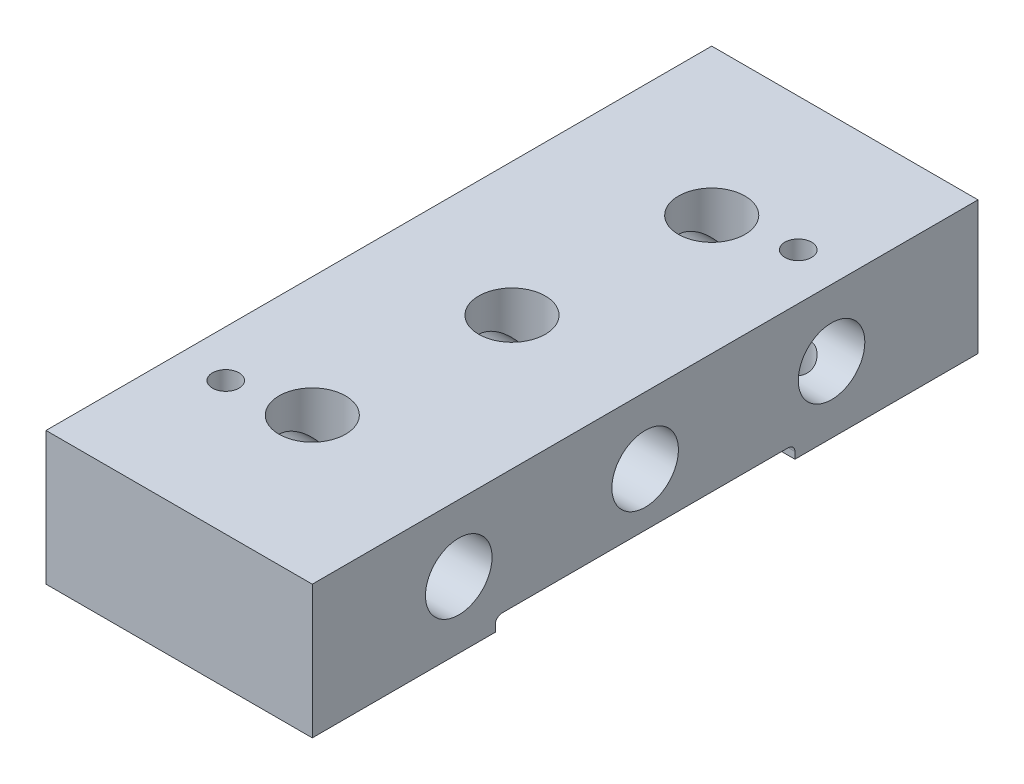
SolidWorks part; units mm, degrees
ref_plane "Plan de face" through (0, 0, 0) normal (0, 0, 1) x (1, 0, 0)
ref_plane "Plan de dessus" through (0, 0, 0) normal (0, 1, 0) x (1, 0, 0)
ref_plane "Plan de droite" through (0, 0, 0) normal (1, 0, 0) x (0, 0, -1)
sketch "Esquisse1" plane through (0, 0, 0) normal (0, 1, 0) x (1, 0, 0)
  line L0 (10, 50) -> (10, 0) construction
  line L1 (0, 0) -> (20, 0)
  line L2 (0, 0) -> (0, 50)
  line L3 (0, 50) -> (20, 50)
  line L4 (20, 0) -> (20, 50)
  line L5 (11, 39) -> (10, 39) construction
  line L6 (0.7507, 0.7524) -> (18.7507, 0.7524) construction
  line L7 (9, 11) -> (10, 11) construction
  line L8 (11, 39) -> (11, 50) construction
  line L9 (9, 11) -> (9, 0) construction
  circle A0 centre (10, 25) radius 2.5
  circle A1 centre (11, 39) radius 2.5
  circle A2 centre (9, 11) radius 2.5
  circle A3 centre (16.5, 40) radius 1
  circle A4 centre (3.5, 10) radius 1
  dimension "D4" = 5
  dimension "D5" = 5
  dimension "D6" = 5
  dimension "D14" = 2
  dimension "D15" = 2
  dimension "D1" = 50
  dimension "D2" = 20
  dimension "D3" = 18
  dimension "D7" = 28
  dimension "D8" = 14
  dimension "D9" = 2
  dimension "D10" = 1
  dimension "D11" = 1
  dimension "D12" = 6.5
  dimension "D13" = 6.5
extrude "Boss.-Extru.1" add sketch "Esquisse1" along normal blind 10
sketch "Esquisse2" plane through (20, 0, 0) normal (1, 0, 0) x (0, 0, -1)
  line L0 (0, 5) -> (50, 5) construction
  line L1 (0, 10) -> (0, 0) construction
  line L2 (50, 10) -> (50, 0) construction
  line L3 (39, 5) -> (50, 5) construction
  line L4 (0, 5) -> (11, 5) construction
  circle A0 centre (11, 5) radius 2.5
  circle A1 centre (25, 5) radius 2.5
  circle A2 centre (39, 5) radius 2.5
  dimension "D1" = 5
  dimension "D2" = 5
  dimension "D3" = 5
  dimension "D4" = 14
extrude "Enlèv. mat.-Extru.1" cut sketch "Esquisse2" against normal through all
extrude "Enlèv. mat.-Extru.2" cut sketch "Esquisse3" against normal through all
sketch "Esquisse3" plane through (0, -14.2701, -25) normal (-1, 0, 0) x (0, 0, 1)
  line L1 (-11.25, 14.2701) -> (11.25, 14.2701)
  line L2 (-11.25, 14.2701) -> (-11.25, 14.7701)
  line L3 (-10.75, 15.2701) -> (10.75, 15.2701)
  line L4 (11.25, 14.2701) -> (11.25, 14.7701)
  line L5 (11.25, 14.5201) -> (25, 14.5201) construction
  line L7 (-11.25, 14.5201) -> (-25, 14.5201) construction
  arc A0 (-11.25, 14.7701) -> (-10.75, 15.2701) centre (-10.75, 14.7701) cw
  arc A1 (10.75, 15.2701) -> (11.25, 14.7701) centre (10.75, 14.7701) cw
  point P17 (-11.25, 15.2701)
  point P20 (11.25, 15.2701)
